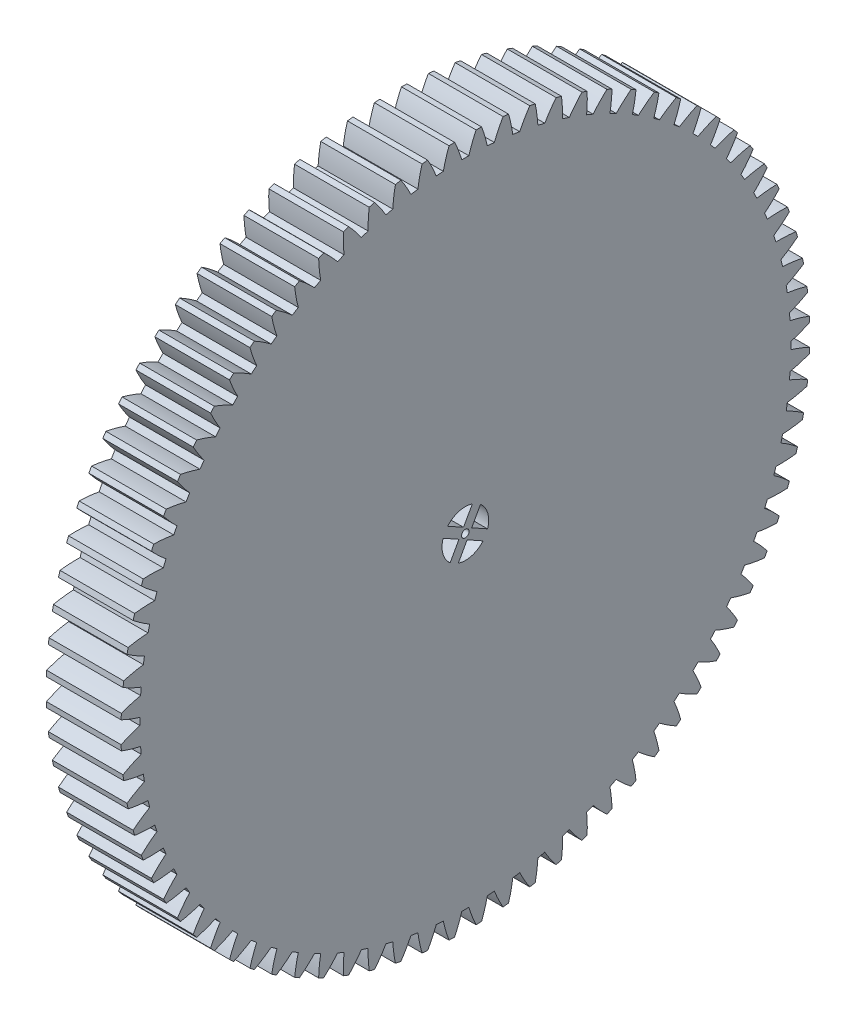
SolidWorks part; units mm, degrees
ref_plane "Plane1" through (0, 0, 0) normal (0, 0, 1) x (1, 0, 0)
ref_plane "Plane2" through (0, 0, 0) normal (0, 1, 0) x (1, 0, 0)
ref_plane "Plane3" through (0, 0, 0) normal (1, 0, 0) x (0, 0, -1)
other "Configuration Table"
sketch "HoldingSke" plane through (0, 0, 0) normal (0, 1, 0) x (1, 0, 0)
  line L0 (0, 0) -> (0.1929, -1.0942)
  line L1 (-15, 0) -> (100, 0) construction
  line L2 (0, 0) -> (-2.1039, 2.3779)
  line L3 (0, 0) -> (-11.863, 4.5341)
  line L4 (0, 0) -> (1.4996, 8.5048)
  line L5 (0, 0) -> (-46.8476, -17.4728)
  line L6 (0, 0) -> (-6.6317, -4.4744)
  line L7 (-2.1039, 2.3779) -> (8.6588, 51.2067)
  line L8 (-76.2, 54.61) -> (-76.1, 54.61)
  line L9 (-71.009, 38.7566) -> (-53.1078, 45.2721)
  line L10 (-76.2, 71.12) -> (104.1128, 71.12)
  line L11 (0, 0) -> (-8, 0)
  line L12 (-76.2, 101.6) -> (-76.166, 101.6)
  line L13 (24.9733, 27.94) -> (52.9518, 28.4284)
  line L14 (24.9733, 27.94) -> (24.9743, 27.94)
  line L15 (24.9733, 27.94) -> (100.4006, 29.5858)
  line L16 (-63.627, -0.9) -> (-12.827, -0.9)
  circle A0 centre (0, 0) radius 0.4
  circle A1 centre (0, 0) radius 16.874
  circle A2 centre (0, 0) radius 37.5
  circle A3 centre (0, 0) radius 0.4
  dimension "MHD" = 33.748
  dimension "Hub_dia" = 75
  dimension "Bore" = 0.8
  dimension "MBD" = 0.8
  dimension "Num_teeth" = 80
  dimension "Pitch" = 1.1111
  dimension "Overall_len" = 50
  dimension "Show_teeth" = 80
  dimension "Thickness" = 8
  dimension "OAL" = 50.0009
  dimension "T_dim" = 0.1
  dimension "Ap" = 20
  dimension "H" = 19.05
  dimension "Pitch_radius" = 180.3128
  dimension "Width" = 8
  dimension "Backlash" = 0.034
  dimension "Addendum_fac" = 1
  dimension "Dedendum_fac" = 1.25
  dimension "Clearance_fac" = 0.25
  dimension "Dedendum_add" = 0.001
  dimension "Module" = 0.9
sketch "BasProSke" plane through (0, 0, 0) normal (0, 1, 0) x (1, 0, 0)
  line L0 (-10, 0) -> (60, 0) construction
  line L1 (0, 0) -> (0, 36.9)
  line L2 (0, 0) -> (8, 0)
  line L3 (8, 0) -> (8, 36.9)
  line L4 (8, 36.9) -> (0, 36.9)
  dimension "Thickness" = 8
  dimension "Diameter" = 73.8
revolve "Base-Revolve" add sketch "BasProSke" angle 360 about L0
sketch "TooCutSke" plane through (0, 0, 0) normal (1, 0, 0) x (0, 0, -1)
  line L1 (0, 0) -> (0, 107) construction
  line L2 (0, 0) -> (-0.7663, 35.9918) construction
  line L3 (0, 0) -> (-2.8262, 71.9329) construction
  line L4 (-0.7663, 35.9918) -> (-1.4131, 35.9664) construction
  arc A0 (0.3781, 34.8719) -> (-0.3781, 34.8719) centre (0, 0) ccw
  arc A1 (1.1635, 36.9071) -> (-1.1635, 36.9071) centre (0, 0) ccw
  circle A2 centre (0, 0) radius 36 construction
  circle A3 centre (0, 0) radius 33.8289 construction
  arc A4 (-0.3781, 34.8719) -> (-1.1635, 36.9071) centre (-14.1665, 30.7198) ccw
  arc A5 (1.1635, 36.9071) -> (0.3781, 34.8719) centre (14.1665, 30.7198) ccw
  dimension "Root_dia" = 69.748
  dimension "Overcut_dia" = 73.8508
  dimension "Pitch_dia" = 72
  dimension "Base_dia" = 67.6579
  dimension "Flank_rad" = 14.4
  dimension "Half_ang" = 2.25
  dimension "Half_CT" = 0.6473
extrude "ToothCut" cut sketch "TooCutSke" along normal through all
fillet "Breaks" [suppressed] radius 0.018
fillet "RootFillets" [suppressed] radius 0.226
pattern_circular "TeethCuts" count 80 every 4.5 about axis through (-10, 0, 0) along (1, 0, 0) of "ToothCut", "RootFillets", "Breaks"
sketch "HubNeaOneSke" plane through (0, 0, 0) normal (-1, 0, 0) x (0, 0, 1)
  circle A0 centre (0, 0) radius 16.874
  dimension "Diameter" = 33.748
extrude "HubNearOne" [suppressed] add sketch "HubNeaOneSke" along normal blind 42.0009
sketch "HubNeaBotSke" plane through (0, 0, 0) normal (-1, 0, 0) x (0, 0, 1)
  circle A0 centre (0, 0) radius 16.874
  dimension "Diameter" = 33.748
extrude "HubNearBoth" [suppressed] add sketch "HubNeaBotSke" along normal blind 21.0004
ref_plane "FarPln" through (8, 0, 0) normal (1, 0, 0) x (0, 0, -1)
sketch "HubFarSke" plane through (8, 0, 0) normal (1, 0, 0) x (0, 0, -1)
  circle A0 centre (0, 0) radius 16.874
  dimension "Diameter" = 33.748
extrude "HubFar" [suppressed] add sketch "HubFarSke" along normal blind 21.0004
sketch "BorSke" plane through (0, 0, 0) normal (1, 0, 0) x (0, 0, -1)
  circle A0 centre (0, 0) radius 0.4
  dimension "Diameter" = 0.8
extrude "Bore" cut sketch "BorSke" along normal mid plane 100.0017
sketch "KeySke" plane through (0, 0, 0) normal (1, 0, 0) x (0, 0, -1)
  line L0 (-0.05, 0) -> (-0.05, 0.5)
  line L1 (-0.05, 0.5) -> (0.05, 0.5)
  line L2 (0.05, 0.5) -> (0.05, 0)
  line L3 (0, 0) -> (0, 34) construction
  line L4 (-0.05, 0) -> (0.05, 0)
  dimension "Offset" = 0.5
  dimension "Width" = 0.1
extrude "Keyway" [suppressed] cut sketch "KeySke" along normal mid plane 100.0017
pattern_circular "Keyway2" [suppressed] count 2 every 90 about axis through (-10, 0, 0) along (1, 0, 0)
sketch "Sketch1" plane through (8, 0, 0) normal (1, 0, 0) x (0, 0, -1)
  line L0 (-0.7554, -2.3831) -> (0.1934, -0.6801)
  line L1 (0.1934, -0.6801) -> (1.8964, -1.629)
  line L2 (2.3831, -0.7554) -> (0.6801, 0.1934)
  line L3 (0.6801, 0.1934) -> (1.629, 1.8964)
  line L4 (0.7554, 2.3831) -> (-0.1934, 0.6801)
  line L5 (-0.1934, 0.6801) -> (-1.8964, 1.629)
  line L6 (-2.3831, 0.7554) -> (-0.6801, -0.1934)
  line L7 (-0.6801, -0.1934) -> (-1.629, -1.8964)
  circle A0 centre (0, 0) radius 2.5 construction
  circle A1 centre (0, 0) radius 2.5
extrude "Cut-Extrude1" cut sketch "Sketch1" against normal up to vertex (8 mm away) contours L4 A1 L5 | L6 A1 L7 | L0 A1 L1 | L2 A1 L3 up to point (0, 33.0483, 11.1357)
equation "' \"Module@HoldingSke\" = 6.35"
equation "' \"Num_teeth@HoldingSke\" = 12"
equation "' \"Ap@HoldingSke\" =  20"
equation "' \"Ap@HoldingSke\" = 20"
equation "' \"Width@HoldingSke\" = 0.5 * 25.4"
equation "' \"Hub_dia@HoldingSke\"= 1 * 25.4"
equation "' \"Hub_dia@HoldingSke\" = 1 * 25.4"
equation "' \"Overall_len@HoldingSke\" = 1.0 * 25.4"
equation "' \"Bore@HoldingSke\" = 0.75 * 25.4"
equation "' \"T_dim@HoldingSke\" = 0.1 * 25.4"
equation "' \"Width@KeySke\" = 0.25 * 25.4"
equation "' \"Show_teeth@HoldingSke\" = 13"
equation "' \"Backlash@HoldingSke\" = 0.009 * 25.4"
equation "' \"Addendum_fac@HoldingSke\" = 1.0"
equation "' \"Dedendum_fac@HoldingSke\" = 1.25"
equation "' \"Dedendum_add@HoldingSke\" = 0.00005 * 25.4"
equation "' \"Clearance_fac@HoldingSke\" = 0.25"
equation "\"Pitch@HoldingSke\"= 1 / \"Module@HoldingSke\""
equation "\"Overcut_dia@TooCutSke\" = (\"Num_teeth@HoldingSke\" + 2 * \"Addendum_fac@HoldingSke\") / \"Pitch@HoldingSke\" + 0.002 * 25.4"
equation "\"Pitch_dia@TooCutSke\" = \"Num_teeth@HoldingSke\" / \"Pitch@HoldingSke\""
equation "\"Base_dia@TooCutSke\" = \"Num_teeth@HoldingSke\" / \"Pitch@HoldingSke\" * cos((\"Ap@HoldingSke\"  * 3.14159265 / 180))"
equation "\"Root_dia@TooCutSke\" = (\"Num_teeth@HoldingSke\" + 2) / \"Pitch@HoldingSke\" - 2 * (\"Addendum_fac@HoldingSke\" + \"Dedendum_fac@HoldingSke\") / \"Pitch@HoldingSke\" - \"Dedendum_add@HoldingSke\" * 2"
equation "\"Half_ang@TooCutSke\" = 180 / \"Num_teeth@HoldingSke\""
equation "\"Half_CT@TooCutSke\" = \"Num_teeth@HoldingSke\" / \"Pitch@HoldingSke\" * sin((3.14159265 / 2 / \"Num_teeth@HoldingSke\")) / 2 - 7 * \"Backlash@HoldingSke\" / 4"
equation "\"Flank_rad@TooCutSke\" = \"Num_teeth@HoldingSke\" / \"Pitch@HoldingSke\" / 5"
equation "\"Radius@RootFillets\" = \"Clearance_fac@HoldingSke\" / \"Pitch@HoldingSke\" + \"Dedendum_add@HoldingSke\""
equation "\"Break_rad@Breaks\" = 0.02 / \"Pitch@HoldingSke\""
equation "\"Thickness@HoldingSke\"= \"Width@HoldingSke\""
equation "\"OAL@HoldingSke\" = \"Thickness@HoldingSke\""
equation "\"MHD@HoldingSke\" = (\"Num_teeth@HoldingSke\" + 2) / \"Pitch@HoldingSke\" - 2 * (\"Addendum_fac@HoldingSke\" + \"Dedendum_fac@HoldingSke\")  / \"Pitch@HoldingSke\" - \"Dedendum_add@HoldingSke\" * 2"
equation "\"MBD@HoldingSke\" = (\"Num_teeth@HoldingSke\" + 2) / \"Pitch@HoldingSke\" - 2 * (\"Addendum_fac@HoldingSke\" + \"Dedendum_fac@HoldingSke\")  / \"Pitch@HoldingSke\" - \"Dedendum_add@HoldingSke\" * 2 - 0.002 * 25.4"
equation "\"MHD@HoldingSke\" = ((sgn( \"MHD@HoldingSke\" - \"Hub_dia@HoldingSke\" )-1)*( \"MHD@HoldingSke\" - \"Hub_dia@HoldingSke\" ))/-2+ \"Hub_dia@HoldingSke\""
equation "\"MBD@HoldingSke\" = ((sgn( \"MBD@HoldingSke\" - \"Bore@HoldingSke\" )-1)*( \"MBD@HoldingSke\" - \"Bore@HoldingSke\" ))/-2+ \"Bore@HoldingSke\""
equation "\"OAL@HoldingSke\" = ((sgn( \"OAL@HoldingSke\" - \"Overall_len@HoldingSke\" )+1)*( \"OAL@HoldingSke\" - \"Overall_len@HoldingSke\" ))/2 + \"Overall_len@HoldingSke\" + 0.000002 * 25.4"
equation "\"Num_teeth@TeethCuts\" = int( \"Show_teeth@HoldingSke\" ) + 1"
equation "\"Num_teeth@TeethCuts\" = ((sgn( \"Num_teeth@TeethCuts\" - \"Num_teeth@HoldingSke\" )-1)*( \"Num_teeth@TeethCuts\" - \"Num_teeth@HoldingSke\" ))/-2+ \"Num_teeth@HoldingSke\""
equation "\"Num_teeth@TeethCuts\"= ( ( sgn ( \"Num_teeth@TeethCuts\" - 2.0 ) + 1 ) * ( \"Num_teeth@HoldingSke\" - 2.0 ) ) / 2 + 2.0"
equation "\"Angle@TeethCuts\" = 360.0 / \"Num_teeth@HoldingSke\""
equation "\"Diameter@BasProSke\" = (\"Num_teeth@HoldingSke\" + 2 * \"Addendum_fac@HoldingSke\") / \"Pitch@HoldingSke\""
equation "\"Thickness@BasProSke\"  = \"Thickness@HoldingSke\""
equation "' \"Fillet_rad@BasProSke\" =  \"Thickness@HoldingSke\" * 0.05"
equation "' \"Fillet_rad@BasProSke\" = \"Thickness@HoldingSke\" * 0.05"
equation "\"MHD@HoldingSke\" = ((sgn( \"MHD@HoldingSke\" - \"Root_dia@TooCutSke\" )-1)*( \"MHD@HoldingSke\" - \"Root_dia@TooCutSke\" ))/-2+ \"Root_dia@TooCutSke\""
equation "\"Diameter@HubNeaOneSke\" = \"MHD@HoldingSke\""
equation "\"Length@HubNearOne\" = \"OAL@HoldingSke\" - \"Thickness@BasProSke\""
equation "\"Diameter@HubNeaBotSke\" = \"MHD@HoldingSke\""
equation "\"Length@HubNearBoth\" = ( \"OAL@HoldingSke\" - \"Thickness@BasProSke\" ) / 2.0"
equation "\"Thickness@FarPln\" = \"Thickness@BasProSke\""
equation "\"Diameter@HubFarSke\" = \"MHD@HoldingSke\""
equation "\"Length@HubFar\" = ( \"OAL@HoldingSke\" - \"Thickness@BasProSke\" ) / 2.0"
equation "\"Diameter@BorSke\" = \"MBD@HoldingSke\""
equation "\"D1@Bore\" = \"OAL@HoldingSke\" * 2.0"
equation "\"D1@Keyway\" = \"OAL@HoldingSke\" * 2.0"
equation "\"Offset@KeySke\" = \"T_dim@HoldingSke\" + \"MBD@HoldingSke\" / 2.0"
